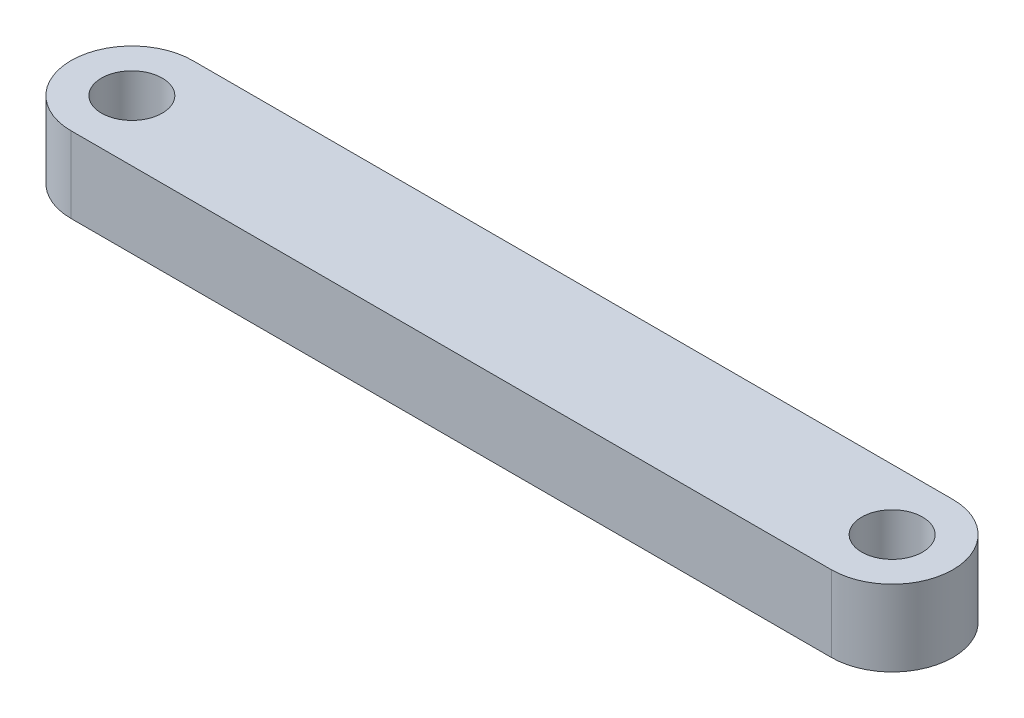
SolidWorks part; units mm, degrees
ref_plane "前基準面" through (0, 0, 0) normal (0, 0, 1) x (1, 0, 0)
ref_plane "上基準面" through (0, 0, 0) normal (0, 1, 0) x (1, 0, 0)
ref_plane "右基準面" through (0, 0, 0) normal (1, 0, 0) x (0, 0, -1)
sketch "草圖1" plane through (0, 0, 0) normal (0, 1, 0) x (1, 0, 0)
  line L0 (-35.9568, 0) -> (39.8148, 0) construction
  line L1 (-25, 0) -> (25, 0) construction
  line L2 (-25, 4) -> (25, 4)
  line L3 (-25, -4) -> (25, -4)
  arc A0 (-25, 4) -> (-25, -4) centre (-25, 0) ccw
  arc A1 (25, -4) -> (25, 4) centre (25, 0) ccw
  circle A2 centre (-25, 0) radius 2
  circle A3 centre (25, 0) radius 2
  point P5 (0, 0)
  dimension "D2" = 2
  dimension "D3" = 4
  dimension "D1" = 50
extrude "填料-伸長1" add sketch "草圖1" along normal blind 5
